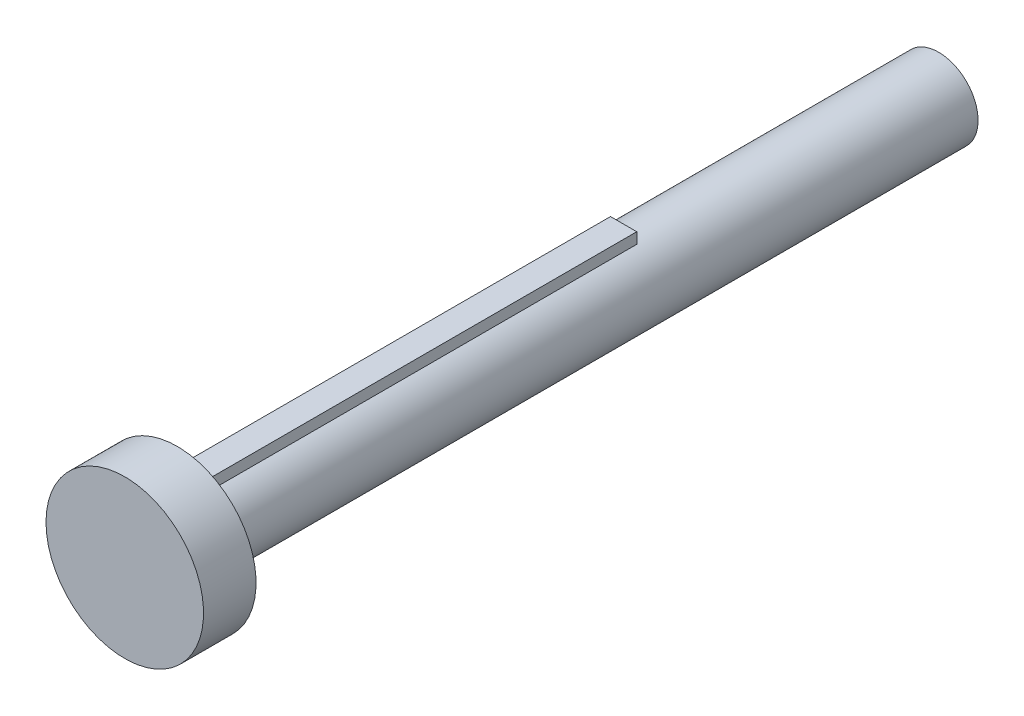
SolidWorks part; units mm, degrees
material "Galvanized Steel"
ref_plane "Front Plane" through (0, 0, 0) normal (0, 0, 1) x (1, 0, 0)
ref_plane "Top Plane" through (0, 0, 0) normal (0, 1, 0) x (1, 0, 0)
ref_plane "Right Plane" through (0, 0, 0) normal (1, 0, 0) x (0, 0, -1)
sketch "Sketch1" plane through (0, 0, 0) normal (0, 0, 1) x (1, 0, 0)
  line L0 (-5, 14.1421) -> (-5, 18.3)
  line L1 (5, 18.3) -> (5, 14.1421)
  line L2 (-5, 18.3) -> (5, 18.3)
  arc A0 (-5, 14.1421) -> (5, 14.1421) centre (0, 0) ccw
  dimension "D1" = 15
  dimension "D2" = 10
  dimension "D3" = 18.3
  dimension "D4" = 5
extrude "Boss-Extrude1" add sketch "Sketch1" along normal mid plane 1600
sketch "Sketch2" plane through (0, 0, -800) normal (0, 0, -1) x (-1, 0, 0)
  circle A0 centre (0, 0) radius 25
  dimension "D1" = 50
extrude "Boss-Extrude2" [suppressed] add sketch "Sketch2" along normal mid plane 10
ref_plane "Plane1" through (0, 0, 590) normal (0, 0, 1) x (1, 0, 0)
sketch "Sketch3" plane through (0, 0, 590) normal (0, 0, -1) x (-1, 0, 0)
  circle A0 centre (0, 0) radius 30
  dimension "D1" = 60
extrude "Boss-Extrude3" add sketch "Sketch3" against normal blind 20
mirror "Mirror2" about plane through (0, 0, 0) normal (0, 0, 1) of "Boss-Extrude3"
sketch "Sketch4" plane through (0, 0, -590) normal (0, 0, 1) x (1, 0, 0)
  circle A1 centre (0, 0) radius 30
  circle A2 centre (0, 0) radius 30
  dimension "D1" = 0
extrude "Cut-Extrude1" cut sketch "Sketch4" along normal through all
sketch "Sketch5" plane through (0, 0, -800) normal (0, 0, -1) x (-1, 0, 0)
  circle A0 centre (0, 0) radius 15
  dimension "D1" = 30
extrude "Boss-Extrude4" add sketch "Sketch5" along normal blind 100
sketch "Sketch6" plane through (0, 0, -800) normal (0, 0, -1) x (-1, 0, 0)
  line L3 (5, 14.1421) -> (5, 18.3)
  line L4 (5, 18.3) -> (-5, 18.3)
  line L5 (-5, 18.3) -> (-5, 14.1421)
  line L6 (5, 14.1421) -> (5, 18.3)
  line L7 (5, 18.3) -> (-5, 18.3)
  line L8 (-5, 18.3) -> (-5, 14.1421)
  arc A1 (5, 14.1421) -> (-5, 14.1421) centre (0, 0) ccw
  arc A2 (5, 14.1421) -> (-5, 14.1421) centre (0, 0) ccw
  dimension "D1" = 0
extrude "Cut-Extrude2" cut sketch "Sketch6" against normal blind 20
